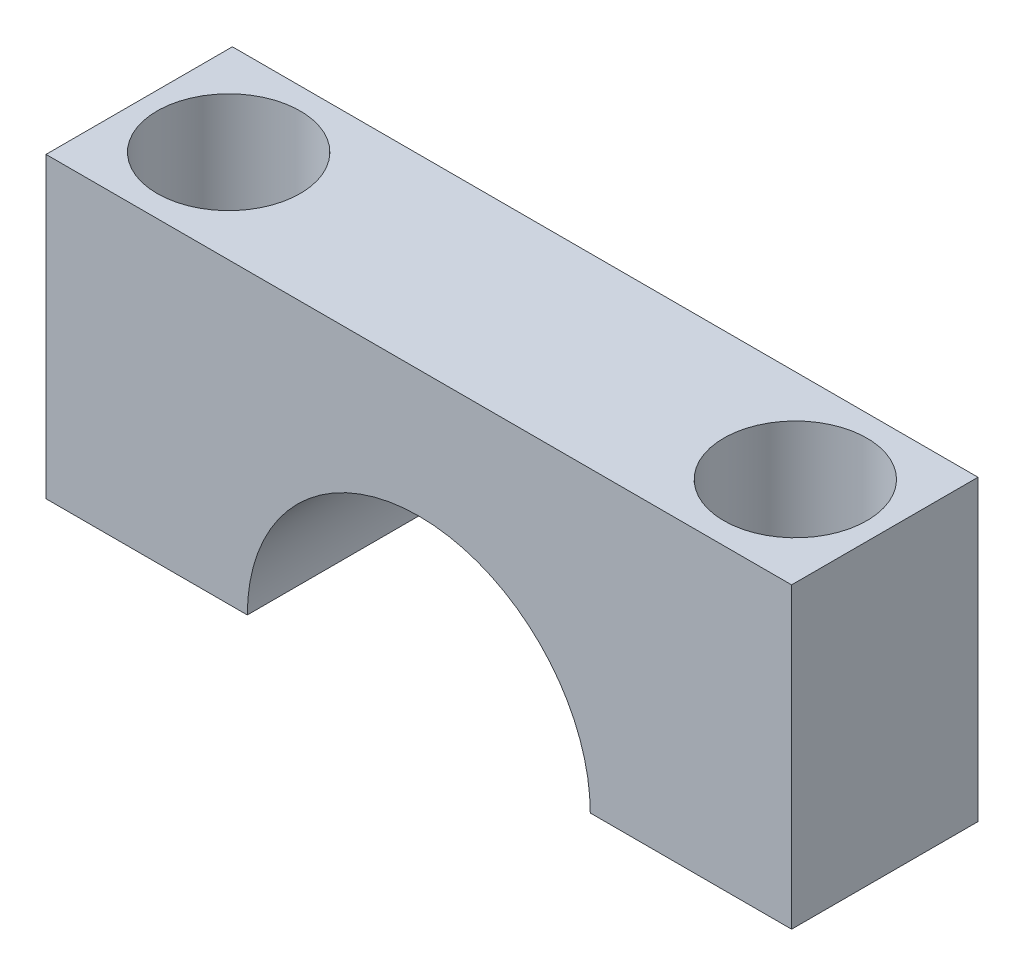
SolidWorks part; units mm, degrees
ref_plane "Front Plane" through (0, 0, 0) normal (0, 0, 1) x (1, 0, 0)
ref_plane "Top Plane" through (0, 0, 0) normal (0, 1, 0) x (1, 0, 0)
ref_plane "Right Plane" through (0, 0, 0) normal (1, 0, 0) x (0, 0, -1)
sketch "Sketch1" plane through (0, 0, 0) normal (0, 0, 1) x (1, 0, 0)
  line L0 (3.429, 0) -> (0, 0)
  line L1 (0, 0) -> (0, 5.08)
  line L2 (0, 5.08) -> (12.7, 5.08)
  line L3 (12.7, 5.08) -> (12.7, 0)
  line L4 (12.7, 0) -> (9.271, 0)
  arc A0 (9.271, 0) -> (3.429, 0) centre (6.35, 0) ccw
  dimension "D2" = 2.921
  dimension "D1" = 6.35
  dimension "D3" = 5.08
  dimension "D4" = 12.7
extrude "Boss-Extrude1" add sketch "Sketch1" along normal blind 3.175
hole_wizard "#2 Clearance Hole1" positions "3DSketch1" profile "Sketch2" hole size "#2" standard "ANSI Inch" end condition through all
sketch3d "3DSketch1"
  line L0 (12.7, 5.08, 3.175) -> (0, 5.08, 3.175) construction
  line L1 (0, 5.08, 3.175) -> (0, 5.08, 0) construction
  line L2 (12.7, 5.08, 3.175) -> (12.7, 5.08, 0) construction
  point P0 (1.524, 5.08, 1.5875)
  point P2 (11.176, 5.08, 1.5875)
  dimension "D1" = 1.5875
  dimension "D2" = 1.524
  dimension "D3" = 1.524
sketch "Sketch2" plane through (1.524, 5.08, 1.5875) normal (1, 0, 0) x (0, 0, 1)
  line L0 (0, 0) -> (0, 5.08)
  line L1 (0, 5.08) -> (1.2192, 5.08)
  line L2 (1.2192, 5.08) -> (1.2192, 0)
  line L5 (1.2192, 0) -> (0, 0)
  line L11 (0, -6.35) -> (0, 107.95) construction
  dimension "Thru Hole Dia." = 2.4384
  dimension "Thru Hole Depth" = 5.08
equation "\"D1@Sketch1\"=\"D4@Sketch1\"/2"
